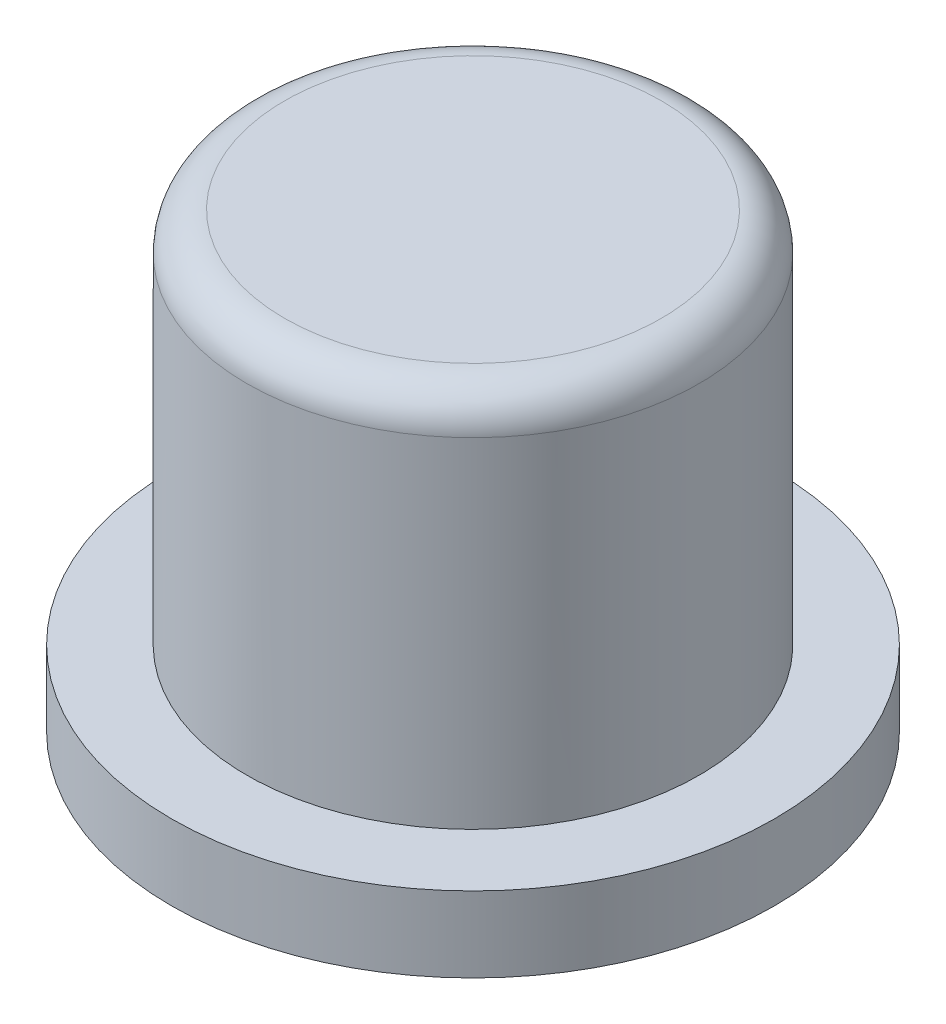
SolidWorks part; units mm, degrees
ref_plane "Front Plane" through (0, 0, 0) normal (0, 0, 1) x (1, 0, 0)
ref_plane "Top Plane" through (0, 0, 0) normal (0, 1, 0) x (1, 0, 0)
ref_plane "Right Plane" through (0, 0, 0) normal (1, 0, 0) x (0, 0, -1)
sketch "Sketch1" plane through (0, 0, 0) normal (0, 1, 0) x (1, 0, 0)
  circle A0 centre (0, 0) radius 38.1
extrude "Boss-Extrude1" add sketch "Sketch1" along normal blind 63.5
sketch "Sketch2" plane through (0, 0, 0) normal (0, -1, 0) x (1, 0, 0)
  circle A0 centre (0, 0) radius 50.8
  dimension "D1" = 101.6
extrude "Boss-Extrude2" add sketch "Sketch2" along normal blind 12.7
fillet "Fillet1" radius 6.35 1 edges at (0, 63.5, 38.1)
